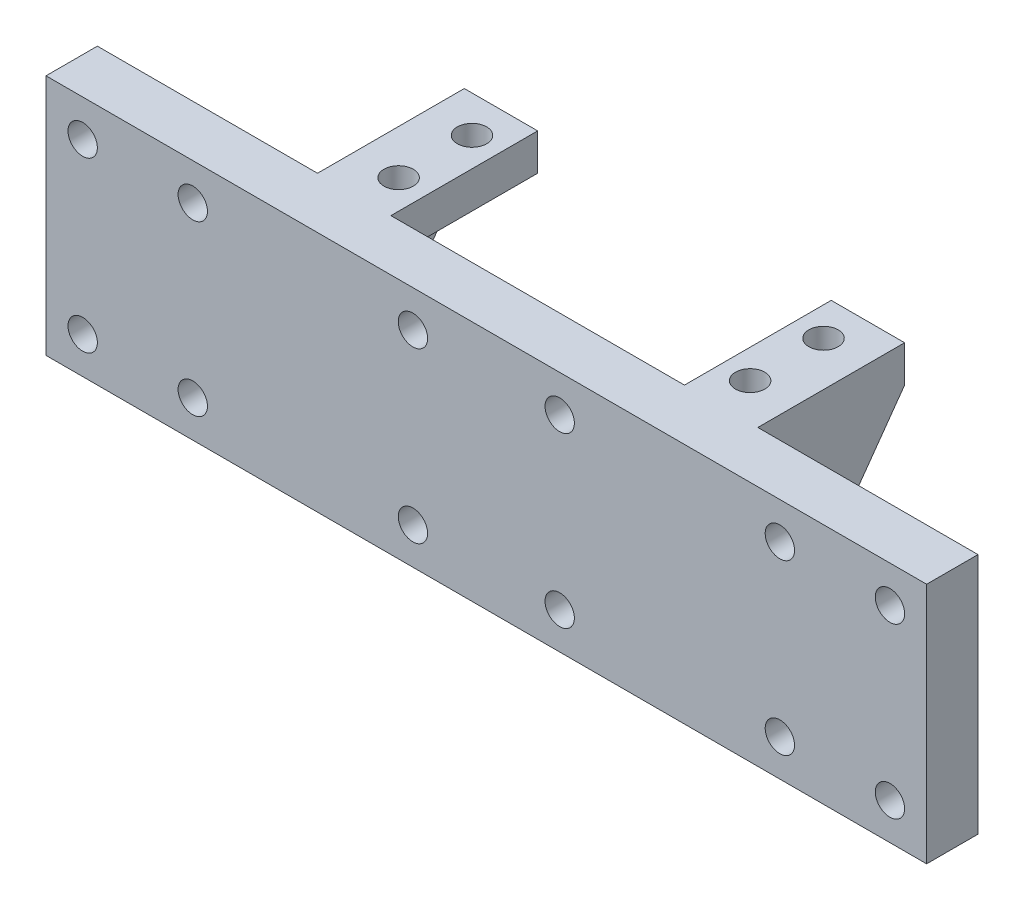
SolidWorks part; units mm, degrees
ref_plane "Front Plane" through (0, 0, 0) normal (0, 0, 1) x (1, 0, 0)
ref_plane "Top Plane" through (0, 0, 0) normal (0, 1, 0) x (1, 0, 0)
ref_plane "Right Plane" through (0, 0, 0) normal (1, 0, 0) x (0, 0, -1)
sketch "Sketch2" plane through (0, 0, 0) normal (0, 1, 0) x (1, 0, 0)
  line L1 (0, 0) -> (40, 0) construction
  line L2 (0, 0) -> (0, 20) construction
  line L3 (0, 20) -> (40, 20) construction
  line L4 (40, 0) -> (40, 20) construction
  line L5 (0, 20) -> (-8, 20)
  line L6 (0, 20) -> (0, 0)
  line L7 (0, 0) -> (-8, 0)
  line L8 (-8, 20) -> (-8, 0)
  line L9 (40, 0) -> (48, 0)
  line L10 (40, 0) -> (40, 20)
  line L11 (40, 20) -> (48, 20)
  line L12 (48, 0) -> (48, 20)
  line L13 (-8, 0) -> (48, 0)
  line L14 (-8, 0) -> (-8, -7)
  line L15 (-8, -7) -> (48, -7)
  line L16 (48, 0) -> (48, -7)
  line L17 (0, 0) -> (40, 0) construction
  line L18 (0, 0) -> (0, 20) construction
  line L19 (0, 20) -> (40, 20) construction
  line L20 (40, 0) -> (40, 20) construction
  line L21 (0, 0) -> (40, 20) construction
  line L22 (0, 20) -> (40, 0) construction
  line L23 (-8, -7) -> (3.75, -7)
  line L24 (-8, -7) -> (-8, -19.66)
  line L25 (-8, -19.66) -> (3.75, -19.66)
  line L26 (3.75, -7) -> (3.75, -19.66)
  line L27 (16.85, -7) -> (28.6, -7)
  line L28 (16.85, -7) -> (16.85, -19.66)
  line L29 (16.85, -19.66) -> (28.6, -19.66)
  line L30 (28.6, -7) -> (28.6, -19.66)
  point P8 (20, 10)
  point P21 (3.75, -19.6986)
  dimension "D1" = 8
  dimension "D2" = 20
  dimension "D3" = 40
  dimension "D4" = 12.66
  dimension "D5" = 3.75
  dimension "D6" = 13.1
  dimension "D7" = 7
  dimension "D8" = 11.75
extrude "Boss-Extrude1" add sketch "Sketch2" along normal blind 5 contours L5 L8 L7 L6 | L16 L9 L13 L7 L14 L15 | L26 L15 L24 L25 | L30 L15 L28 L29 | L9 L12 L11 L10
sketch "Sketch3" plane through (0, 0, 0) normal (0, -1, 0) x (1, 0, 0)
  line L0 (0, 0) -> (40, 0) construction
  line L1 (-8, 19.66) -> (3.75, 19.66)
  line L2 (-8, 19.66) -> (-8, 0)
  line L3 (-8, 0) -> (3.75, 0)
  line L4 (3.75, 19.66) -> (3.75, 0)
  line L5 (28.6, 7) -> (28.6, 19.66) construction
  line L6 (16.85, 19.66) -> (28.6, 19.66)
  line L7 (16.85, 19.66) -> (16.85, 0)
  line L8 (16.85, 0) -> (28.6, 0)
  line L9 (28.6, 19.66) -> (28.6, 0)
  line L11 (3.75, 0) -> (16.85, 0)
  line L12 (3.75, 0) -> (3.75, 7)
  line L13 (3.75, 7) -> (16.85, 7)
  line L14 (16.85, 0) -> (16.85, 7)
  line M15 (0, 0) -> (40, 0)
  line M20 (28.6, 7) -> (28.6, 19.66)
  line M21 (28.6, 19.66) -> (16.85, 19.66)
  line M22 (16.85, 19.66) -> (16.85, 7)
  line M23 (16.85, 7) -> (3.75, 7)
  line M24 (3.75, 7) -> (3.75, 19.66)
  line M25 (3.75, 19.66) -> (-8, 19.66)
  line M26 (-8, 19.66) -> (-8, -20)
extrude "Boss-Extrude2" add sketch "Sketch3" along normal blind 28 contours L4 L3 M24 M25 M26 M15 | L7 L4 M23 M15 | L9 L7 M20 M21 M22 M15
sketch "Sketch4" plane through (0, -28, 0) normal (0, -1, 0) x (1, 0, 0)
  line L1 (-8, 19.66) -> (-2.25, 19.66)
  line L2 (-8, 19.66) -> (-8, 7)
  line L3 (-8, 7) -> (-2.25, 7)
  line L4 (-2.25, 19.66) -> (-2.25, 7)
  line L5 (28.6, 19.66) -> (22.85, 19.66)
  line L6 (28.6, 19.66) -> (28.6, 7)
  line L7 (28.6, 7) -> (22.85, 7)
  line L8 (22.85, 19.66) -> (22.85, 7)
  line L9 (3.75, 19.66) -> (3.75, 7) construction
  line L10 (16.85, 19.66) -> (16.85, 7) construction
  line L11 (16.85, 7) -> (3.75, 7) construction
  dimension "D1" = 6
  dimension "D2" = 6
extrude "Cut-Extrude1" cut sketch "Sketch4" against normal through all
sketch "Sketch5" plane through (-2.25, 0, 0) normal (-1, 0, 0) x (0, 0, 1)
  line L0 (13.33, 5) -> (13.33, -28) construction
  line L1 (7, 5) -> (19.66, 5) construction
  line L2 (7, -28) -> (19.66, -28) construction
  circle A0 centre (13.33, -2) radius 2
  circle A1 centre (13.33, -21) radius 2
  circle A2 centre (13.33, -11.5) radius 2
  dimension "D1" = 4
  dimension "D2" = 7
  dimension "D3" = 7
extrude "Cut-Extrude2" cut sketch "Sketch5" against normal through all
sketch "Sketch6" plane through (0, 0, 0) normal (0, -1, 0) x (1, 0, 0)
  line L0 (40, -10) -> (0, -10) construction
  line L1 (-3.95, -5) -> (43.95, -5) construction
  line L2 (-3.95, -5) -> (-3.95, -15) construction
  line L3 (-3.95, -15) -> (43.95, -15) construction
  line L4 (43.95, -5) -> (43.95, -15) construction
  line L5 (40, 0) -> (40, -20) construction
  line L6 (0, -20) -> (0, 0) construction
  line L7 (20, -10) -> (20, -15) construction
  line L8 (20, -10) -> (20, -5) construction
  circle A0 centre (43.95, -5) radius 2
  circle A1 centre (43.95, -15) radius 2
  circle A2 centre (-3.95, -5) radius 2
  circle A3 centre (-3.95, -15) radius 2
  dimension "D3" = 4
  dimension "D1" = 10
  dimension "D2" = 47.9
extrude "Cut-Extrude3" cut sketch "Sketch6" against normal through all contours A2
sketch "Sketch7" plane through (28.6, 0, 0) normal (1, 0, 0) x (0, 0, -1)
  line L4 (-7, 0) -> (-7, -28)
  line L5 (-7, -28) -> (0, -28)
  line L6 (0, -28) -> (0, 0)
  line L7 (0, 0) -> (-7, 0)
  line L8 (-7, 0) -> (-7, -28)
  line L9 (-7, -28) -> (0, -28)
  line L10 (0, -28) -> (0, 0)
  line L11 (0, 0) -> (-7, 0)
  dimension "D1" = 0
extrude "Boss-Extrude3" add sketch "Sketch7" along normal up to surface (19.4 mm away) up to face at (48, 2.5, -6.5)
sketch "Sketch8" plane through (48, 0, 0) normal (1, 0, 0) x (0, 0, -1)
  line L1 (-7, -28) -> (20, -28)
  line L2 (-7, -28) -> (-7, 5)
  line L3 (-7, 5) -> (20, 5)
  line L4 (20, -28) -> (20, 5)
extrude "Boss-Extrude4" add sketch "Sketch8" along normal blind 2
sketch "Sketch9" plane through (-8, 0, 0) normal (-1, 0, 0) x (0, 0, 1)
  line L1 (-20, 5) -> (7, 5)
  line L2 (-20, 5) -> (-20, -28)
  line L3 (-20, -28) -> (7, -28)
  line L4 (7, 5) -> (7, -28)
extrude "Boss-Extrude5" add sketch "Sketch9" along normal blind 2
sketch "Sketch10" plane through (48, 0, 0) normal (-1, 0, 0) x (0, 0, 1)
  line L0 (-20, 0) -> (0, -28)
  line L1 (0, -28) -> (-20, -28)
  line L2 (-20, -28) -> (-20, 0)
extrude "Cut-Extrude4" cut sketch "Sketch10" against normal through all and the other way through all
sketch "Sketch12" plane through (-2.25, 0, 0) normal (-1, 0, 0) x (0, 0, 1)
  line L1 (19.66, -28) -> (7, -28)
  line L2 (19.66, -28) -> (19.66, 5)
  line L3 (19.66, 5) -> (7, 5)
  line L4 (7, -28) -> (7, 5)
extrude "Cut-Extrude5" cut sketch "Sketch12" against normal through all
sketch "Sketch13" plane through (0, 5, 0) normal (0, 1, 0) x (1, 0, 0)
  line L0 (0, 0) -> (40, 0) construction
  line L1 (-10, -7) -> (-40, -7)
  line L2 (-10, -7) -> (-10, 0)
  line L3 (-10, 0) -> (-40, 0)
  line L4 (-40, -7) -> (-40, 0)
  line L5 (50, -7) -> (80, -7)
  line L6 (50, -7) -> (50, 0)
  line L7 (50, 0) -> (80, 0)
  line L8 (80, -7) -> (80, 0)
  point P12 (-43.6386, 0)
  dimension "D1" = 30
extrude "Boss-Extrude6" add sketch "Sketch13" against normal up to surface (33 mm away) up to face at (20, -28, 2.3333)
sketch "Sketch14" plane through (0, 0, 0) normal (0, 0, -1) x (-1, 0, 0)
  line L0 (-20, 5) -> (-20, -28) construction
  line L1 (0, 5) -> (-40, 5) construction
  line L2 (8, -28) -> (-48, -28) construction
  line L3 (40, -28) -> (40, 5) construction
  line L4 (35, 0) -> (-75, 0) construction
  line L5 (35, 0) -> (35, -23) construction
  line L6 (35, -23) -> (-75, -23) construction
  line L7 (-75, 0) -> (-75, -23) construction
  line L8 (35, 0) -> (-75, -23) construction
  line L9 (35, -23) -> (-75, 0) construction
  line L10 (-60, 0) -> (20, 0) construction
  line L11 (-60, 0) -> (-60, -23) construction
  line L12 (-60, -23) -> (20, -23) construction
  line L13 (20, 0) -> (20, -23) construction
  line L14 (-60, 0) -> (20, -23) construction
  line L15 (-60, -23) -> (20, 0) construction
  line L16 (-10, 0) -> (-30, 0) construction
  line L17 (-10, 0) -> (-10, -23) construction
  line L18 (-10, -23) -> (-30, -23) construction
  line L19 (-30, 0) -> (-30, -23) construction
  line L20 (-10, 0) -> (-30, -23) construction
  line L21 (-10, -23) -> (-30, 0) construction
  line L22 (10, -28) -> (40, -28) construction
  line L23 (10, -28) -> (10, 5) construction
  circle A0 centre (35, -23) radius 2
  circle A1 centre (20, -23) radius 2
  circle A2 centre (20, 0) radius 2
  circle A3 centre (35, 0) radius 2
  circle A4 centre (-10, 0) radius 2
  circle A5 centre (-10, -23) radius 2
  circle A6 centre (-30, -23) radius 2
  circle A7 centre (-30, 0) radius 2
  circle A8 centre (-60, 0) radius 2
  circle A9 centre (-60, -23) radius 2
  circle A10 centre (-75, -23) radius 2
  circle A11 centre (-75, 0) radius 2
  point P4 (-20, -11.5)
  point P11 (-20, -11.5)
  point P12 (-20, -11.5)
  dimension "D5" = 4
  dimension "D1" = 5
  dimension "D2" = 5
  dimension "D3" = 10
  dimension "D4" = 10
extrude "Cut-Extrude6" cut sketch "Sketch14" against normal through all
